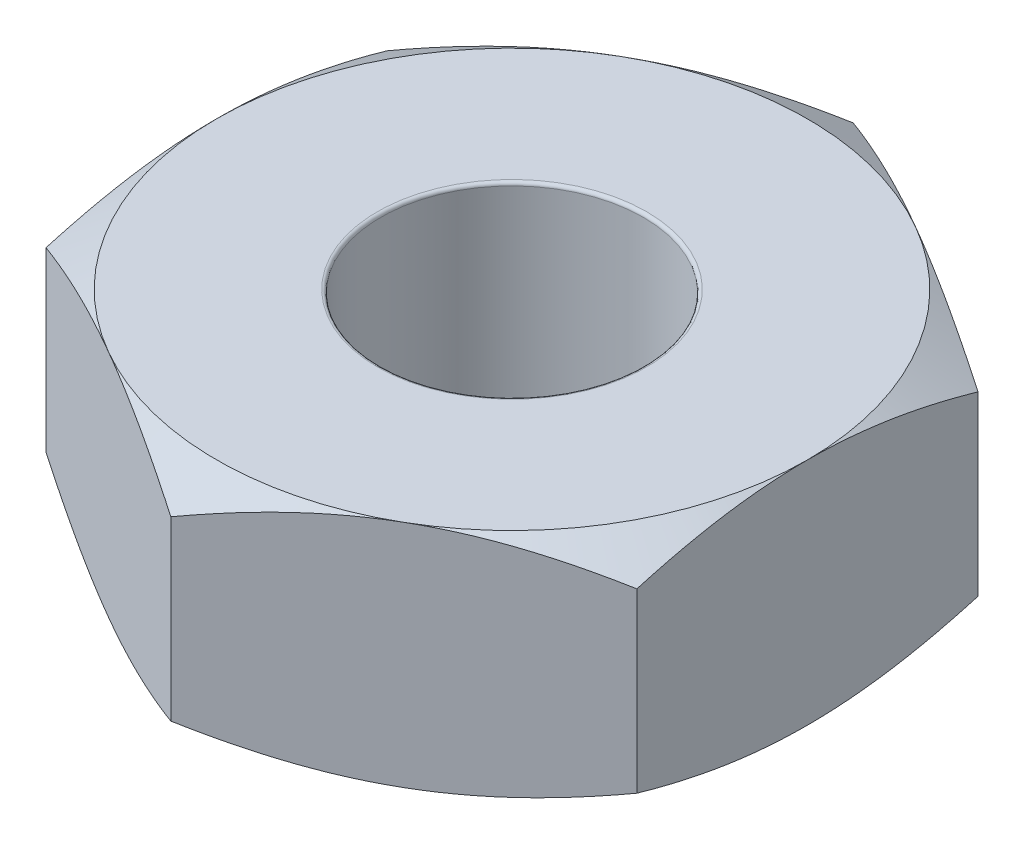
SolidWorks part; units mm, degrees
ref_plane "Front Plane" through (0, 0, 0) normal (0, 0, 1) x (1, 0, 0)
ref_plane "Top Plane" through (0, 0, 0) normal (0, 1, 0) x (1, 0, 0)
ref_plane "Right Plane" through (0, 0, 0) normal (1, 0, 0) x (0, 0, -1)
sketch "Sketch1" plane through (0, 0, 0) normal (0, 1, 0) x (1, 0, 0)
  line L1 (0, 2.5981) -> (-2.25, 1.299)
  line L2 (-2.25, 1.299) -> (-2.25, -1.299)
  line L3 (-2.25, -1.299) -> (0, -2.5981)
  line L4 (0, -2.5981) -> (2.25, -1.299)
  line L5 (2.25, -1.299) -> (2.25, 1.299)
  line L6 (2.25, 1.299) -> (0, 2.5981)
  circle A0 centre (0, 0) radius 1
  circle A1 centre (0, 0) radius 2.25 construction
  point P3 (0, 0)
  dimension "D1" = 2
  dimension "D2" = 4.5
extrude "Boss-Extrude1" add sketch "Sketch1" along normal blind 1.75
sketch "Sketch2" plane through (0, 1.75, 0) normal (0, 1, 0) x (1, 0, 0)
  circle A0 centre (0, 0) radius 2.25 construction
  circle A1 centre (0, 0) radius 2.25
extrude "Cut-Extrude1" cut sketch "Sketch2" against normal blind 1.75 draft 60 flip side to cut
ref_plane "Plane1" through (0, 0.875, 0) normal (0, 1, 0) x (1, 0, 0)
mirror "Mirror1" about plane through (0, 0.875, 0) normal (0, 1, 0) of "Cut-Extrude1"
fillet "Fillet1" radius 0.025 2 edges at (0, 0, 1) (0, 1.75, 1)
